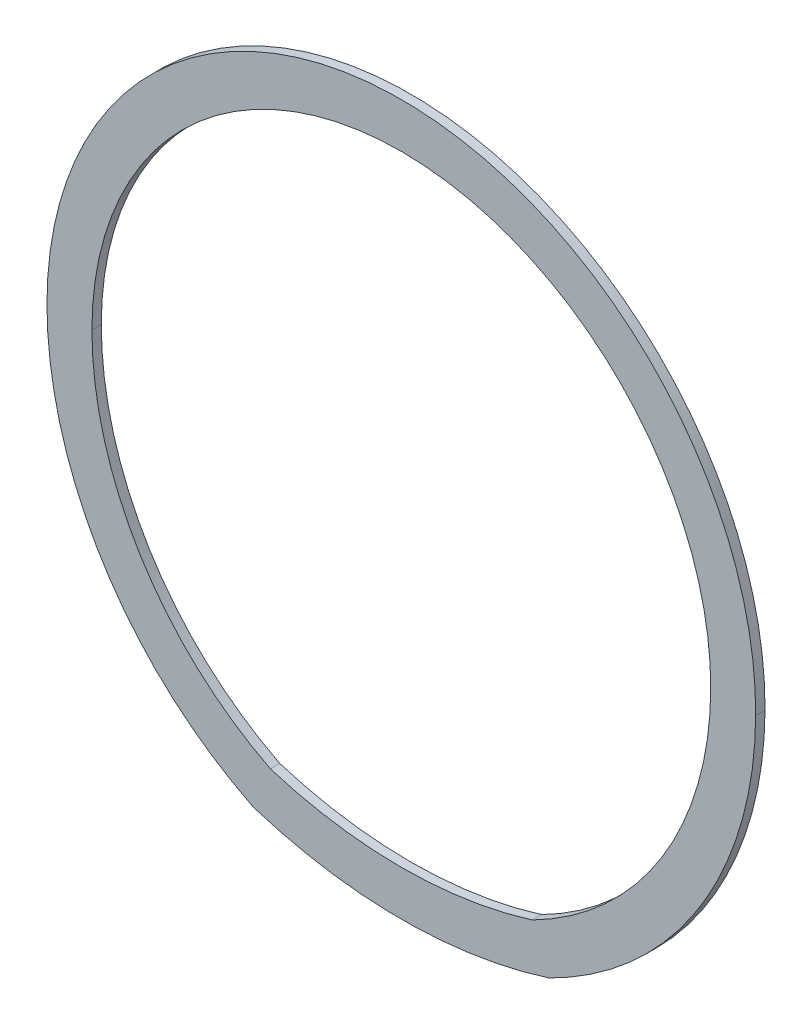
SolidWorks part; units mm, degrees
material "Balsa"
ref_plane "Front Plane" through (0, 0, 0) normal (0, 0, 1) x (1, 0, 0)
ref_plane "Top Plane" through (0, 0, 0) normal (0, 1, 0) x (1, 0, 0)
ref_plane "Right Plane" through (0, 0, 0) normal (1, 0, 0) x (0, 0, -1)
sketch "Sketch2" plane through (0, 0, 0) normal (0, 0, 1) x (1, 0, 0)
  line L0 (0, 0) -> (0.688, 245.4392) construction
  line L1 (-0.1309, -46.7153) -> (-0.2841, -101.3462) construction
  line L2 (0.0534, 19.05) -> (-169.3081, 19.05) construction
  line L3 (-72.7218, -93.726) -> (74.7111, -93.726) construction
  arc A1 (-120.0989, 19.05) -> (120.2036, 18.3433) centre (0.0534, 19.05) cw
  arc A2 (-120.0989, 19.05) -> (-50.0584, -93.726) centre (5.7147, 19.05) ccw
  arc A3 (-50.0584, -93.726) -> (50.1388, -93.726) centre (0.0402, 63.5) ccw
  arc A4 (120.2036, 18.3433) -> (50.1388, -93.726) centre (-5.6406, 19.0835) cw
  arc A5 (-104.8589, 19.05) -> (104.9639, 18.4329) centre (0.0534, 19.05) cw
  arc A6 (104.9639, 18.4329) -> (44.4049, -79.5534) centre (-5.6406, 19.0835) cw
  arc A7 (-44.324, -79.5535) -> (44.4049, -79.5534) centre (0.0402, 63.5) ccw
  arc A8 (-104.8589, 19.05) -> (-44.324, -79.5535) centre (5.7147, 19.05) ccw
  spline S0 degree 3 poles (-5521.0274, 5583.2546) (-1226.7801, 553.2855) (-196.9505, -260.8007) (69.4764, -82.4823) (75.8596, -77.7331) (81.7614, -72.3621) (85.2966, -68.8071) (85.996, -68.0862) (87.3792, -66.6243) (88.0639, -65.8824) (90.0847, -63.6371) (91.3894, -62.1126) (95.1787, -57.4581) (97.5389, -54.2471) (101.9343, -47.6137) (103.9694, -44.1914) (106.7765, -38.8981) (107.6712, -37.107) (109.3772, -33.4707) (110.1904, -31.6207) (112.481, -26.0415) (113.8153, -22.2742) (116.1105, -14.6467) (117.0712, -10.7866) (118.62, -2.9737) (119.208, 0.9791) (119.8028, 6.9796) (119.953, 8.9949) (120.1541, 13.0067) (120.2055, 15.0081) (120.2151, 20.9991) (119.8425, 28.9519) (118.7088, 36.835) (117.5685, 42.7208) (117.1399, 44.6783) (116.1841, 48.5842) (115.6559, 50.5346) (113.94, 56.3082) (112.6165, 60.0751) (109.6192, 67.4485) (107.9453, 71.055) (104.2453, 78.1066) (102.2192, 81.5518) (99.4588, 85.754) (98.8945, 86.5903) (97.7468, 88.2466) (97.1639, 89.0659) (95.3883, 91.4977) (94.1686, 93.0841) (90.4034, 97.7402) (87.752, 100.7072) (82.1689, 106.369) (79.2371, 109.0639) (74.6247, 112.8977) (73.0514, 114.1408) (70.6363, 115.9521) (69.821, 116.5478) (68.1799, 117.7153) (67.3537, 118.2875) (63.1947, 121.0918) (59.7778, 123.1535) (52.769, 126.9212) (49.1769, 128.6272) (41.816, 131.6806) (38.0473, 133.028) (33.2217, 134.4796) (32.2518, 134.758) (30.3116, 135.2882) (29.34, 135.5404) (26.4206, 136.2591) (24.4685, 136.6873) (18.5945, 137.8219) (14.6552, 138.3782) (6.7301, 139.0933) (2.7444, 139.252) (-2.2675, 139.1959) (-3.2714, 139.172) (-5.2821, 139.0983) (-6.2905, 139.0484) (-9.3072, 138.8606) (-11.3068, 138.6846) (-17.272, 138.0072) (-25.1357, 136.7069) (-32.823, 134.6274) (-38.5216, 132.7724) (-40.41, 132.1048) (-44.1641, 130.6694) (-46.0326, 129.9002) (-465.435, -55.3606) (264.7727, -2591.6725) (2155.1784, -7505.3224) knots -2.450405 -2.450405 -2.450405 -2.450405 0.03125 0.03125 0.0625 0.09375 0.09375 0.101563 0.101563 0.109375 0.109375 0.125 0.125 0.15625 0.15625 0.1875 0.1875 0.203125 0.203125 0.21875 0.21875 0.25 0.25 0.28125 0.28125 0.3125 0.3125 0.328125 0.328125 0.34375 0.34375 0.375 0.40625 0.40625 0.421875 0.421875 0.4375 0.4375 0.46875 0.46875 0.5 0.5 0.53125 0.53125 0.539063 0.539063 0.546875 0.546875 0.5625 0.5625 0.59375 0.59375 0.625 0.625 0.640625 0.640625 0.648438 0.648438 0.65625 0.65625 0.6875 0.6875 0.71875 0.71875 0.75 0.75 0.757813 0.757813 0.765625 0.765625 0.78125 0.78125 0.8125 0.8125 0.84375 0.84375 0.851563 0.851563 0.859375 0.859375 0.875 0.875 0.90625 0.9375 0.9375 0.953125 0.953125 0.96875 0.96875 4.508313 4.508313 4.508313 4.508313 only from (55.8537, -90.8749) to (-58.6671, 123.6507)
  spline S1 degree 3 poles (55.8537, -90.8749) (59.4151, -88.9779) (62.8499, -86.9173) (69.4764, -82.4823) (75.8596, -77.7331) (81.7614, -72.3621) (85.2966, -68.8071) (85.996, -68.0862) (87.3792, -66.6243) (88.0639, -65.8824) (90.0847, -63.6371) (91.3894, -62.1126) (95.1787, -57.4581) (97.5389, -54.2471) (101.9343, -47.6137) (103.9694, -44.1914) (106.7765, -38.8981) (107.6712, -37.107) (109.3772, -33.4707) (110.1904, -31.6207) (112.481, -26.0415) (113.8153, -22.2742) (116.1105, -14.6467) (117.0712, -10.7866) (118.62, -2.9737) (119.208, 0.9791) (119.8028, 6.9796) (119.953, 8.9949) (120.1541, 13.0067) (120.2055, 15.0081) (120.2151, 20.9991) (119.8425, 28.9519) (118.7088, 36.835) (117.5685, 42.7208) (117.1399, 44.6783) (116.1841, 48.5842) (115.6559, 50.5346) (113.94, 56.3082) (112.6165, 60.0751) (109.6192, 67.4485) (107.9453, 71.055) (104.2453, 78.1066) (102.2192, 81.5518) (99.4588, 85.754) (98.8945, 86.5903) (97.7468, 88.2466) (97.1639, 89.0659) (95.3883, 91.4977) (94.1686, 93.0841) (90.4034, 97.7402) (87.752, 100.7072) (82.1689, 106.369) (79.2371, 109.0639) (74.6247, 112.8977) (73.0514, 114.1408) (70.6363, 115.9521) (69.821, 116.5478) (68.1799, 117.7153) (67.3537, 118.2875) (63.1947, 121.0918) (59.7778, 123.1535) (52.769, 126.9212) (49.1769, 128.6272) (41.816, 131.6806) (38.0473, 133.028) (33.2217, 134.4796) (32.2518, 134.758) (30.3116, 135.2882) (29.34, 135.5404) (26.4206, 136.2591) (24.4685, 136.6873) (18.5945, 137.8219) (14.6552, 138.3782) (6.7301, 139.0933) (2.7444, 139.252) (-2.2675, 139.1959) (-3.2714, 139.172) (-5.2821, 139.0983) (-6.2905, 139.0484) (-9.3072, 138.8606) (-11.3068, 138.6846) (-17.272, 138.0072) (-25.1357, 136.7069) (-32.823, 134.6274) (-38.5216, 132.7724) (-40.41, 132.1048) (-44.1641, 130.6694) (-46.0326, 129.9002) (-51.5624, 127.4576) (-55.1595, 125.6458) (-58.6671, 123.6507) knots 0 0 0 0 0.03125 0.03125 0.0625 0.09375 0.09375 0.101563 0.101563 0.109375 0.109375 0.125 0.125 0.15625 0.15625 0.1875 0.1875 0.203125 0.203125 0.21875 0.21875 0.25 0.25 0.28125 0.28125 0.3125 0.3125 0.328125 0.328125 0.34375 0.34375 0.375 0.40625 0.40625 0.421875 0.421875 0.4375 0.4375 0.46875 0.46875 0.5 0.5 0.53125 0.53125 0.539063 0.539063 0.546875 0.546875 0.5625 0.5625 0.59375 0.59375 0.625 0.625 0.640625 0.640625 0.648438 0.648438 0.65625 0.65625 0.6875 0.6875 0.71875 0.71875 0.75 0.75 0.757813 0.757813 0.765625 0.765625 0.78125 0.78125 0.8125 0.8125 0.84375 0.84375 0.851563 0.851563 0.859375 0.859375 0.875 0.875 0.90625 0.9375 0.9375 0.953125 0.953125 0.96875 0.96875 1 1 1 1 construction
  spline S2 degree 3 poles (5694.5744, -5369.3669) (1292.3799, -516.6509) (187.1926, 314.492) (-76.9523, 111.0297) (-81.0984, 107.3558) (-85.9766, 102.3921) (-86.9369, 101.3807) (-88.8267, 99.3202) (-89.7577, 98.2691) (-92.4915, 95.0728) (-94.2304, 92.8907) (-99.2026, 86.1952) (-102.1931, 81.5333) (-106.1993, 74.2476) (-107.4545, 71.77) (-109.2154, 67.9791) (-109.782, 66.7031) (-110.874, 64.1258) (-111.4002, 62.8224) (-113.9097, 56.2871) (-115.5417, 50.9767) (-118.0823, 40.1978) (-118.9908, 34.7292) (-119.6657, 27.7928) (-119.7775, 26.4005) (-119.9543, 23.6055) (-120.0192, 22.2016) (-120.1418, 18.0057) (-120.1286, 15.2199) (-119.8102, 6.8959) (-119.2278, 1.3912) (-117.8014, -6.7994) (-117.2335, -9.5184) (-116.2404, -13.58) (-115.8858, -14.9311) (-115.1288, -17.6274) (-114.7258, -18.9739) (-112.6063, -25.6411) (-108.5276, -35.9696) (-103.1136, -45.6397) (-99.3011, -51.4722) (-98.5171, -52.628) (-96.9053, -54.9182) (-96.0765, -56.0537) (-93.5433, -59.4015) (-91.7865, -61.5635) (-86.3167, -67.8444) (-82.4051, -71.759) (-76.1398, -77.2217) (-73.9848, -78.9742) (-70.6503, -81.498) (-69.5218, -82.3217) (-67.2303, -83.9337) (-66.0665, -84.7222) (540.7318, -480.5341) (3882.3497, 5108.7967) (222.2795, -4616.5222) knots -3.63779 -3.63779 -3.63779 -3.63779 0.0625 0.0625 0.125 0.125 0.140625 0.140625 0.15625 0.15625 0.1875 0.1875 0.25 0.25 0.28125 0.28125 0.296875 0.296875 0.3125 0.3125 0.375 0.375 0.4375 0.4375 0.453125 0.453125 0.46875 0.46875 0.5 0.5 0.5625 0.5625 0.59375 0.59375 0.609375 0.609375 0.625 0.625 0.6875 0.75 0.75 0.765625 0.765625 0.78125 0.78125 0.8125 0.8125 0.875 0.875 0.90625 0.90625 0.921875 0.921875 0.9375 0.9375 9.012836 9.012836 9.012836 9.012836 only from (-58.6671, 123.6507) to (-50.3455, -93.5936)
  spline S3 degree 3 poles (-4578.1193, 6360.5009) (1102.8247, -3189.0685) (1357.3206, -1629.0846) (-2110.3169, 7551.2134) knots -196.711406 -196.711406 -196.711406 -196.711406 209.883914 209.883914 209.883914 209.883914 only from (49.819, -93.8744) to (55.8537, -90.8749)
  spline S4 degree 3 poles (49.819, -93.8744) (51.8584, -92.9316) (53.87, -91.9317) (55.8537, -90.8749) knots 0 0 0 0 1 1 1 1 construction
  spline S5 degree 3 poles (-58.6671, 123.6507) (-63.5487, 120.874) (-68.1774, 117.7887) (-76.9523, 111.0297) (-81.0984, 107.3558) (-85.9766, 102.3921) (-86.9369, 101.3807) (-88.8267, 99.3202) (-89.7577, 98.2691) (-92.4915, 95.0728) (-94.2304, 92.8907) (-99.2026, 86.1952) (-102.1931, 81.5333) (-106.1993, 74.2476) (-107.4545, 71.77) (-109.2154, 67.9791) (-109.782, 66.7031) (-110.874, 64.1258) (-111.4002, 62.8224) (-113.9097, 56.2871) (-115.5417, 50.9767) (-118.0823, 40.1978) (-118.9908, 34.7292) (-119.6657, 27.7928) (-119.7775, 26.4005) (-119.9543, 23.6055) (-120.0192, 22.2016) (-120.1418, 18.0057) (-120.1286, 15.2199) (-119.8102, 6.8959) (-119.2278, 1.3912) (-117.8014, -6.7994) (-117.2335, -9.5184) (-116.2404, -13.58) (-115.8858, -14.9311) (-115.1288, -17.6274) (-114.7258, -18.9739) (-112.6063, -25.6411) (-108.5276, -35.9696) (-103.1136, -45.6397) (-99.3011, -51.4722) (-98.5171, -52.628) (-96.9053, -54.9182) (-96.0765, -56.0537) (-93.5433, -59.4015) (-91.7865, -61.5635) (-86.3167, -67.8444) (-82.4051, -71.759) (-76.1398, -77.2217) (-73.9848, -78.9742) (-70.6503, -81.498) (-69.5218, -82.3217) (-67.2303, -83.9337) (-66.0665, -84.7222) (-60.2073, -88.5441) (-55.3561, -91.2432) (-50.3455, -93.5936) knots 0 0 0 0 0.0625 0.0625 0.125 0.125 0.140625 0.140625 0.15625 0.15625 0.1875 0.1875 0.25 0.25 0.28125 0.28125 0.296875 0.296875 0.3125 0.3125 0.375 0.375 0.4375 0.4375 0.453125 0.453125 0.46875 0.46875 0.5 0.5 0.5625 0.5625 0.59375 0.59375 0.609375 0.609375 0.625 0.625 0.6875 0.75 0.75 0.765625 0.765625 0.78125 0.78125 0.8125 0.8125 0.875 0.875 0.90625 0.90625 0.921875 0.921875 0.9375 0.9375 1 1 1 1 construction
  spline S6 degree 3 poles (-1759.0643, 7695.5768) (129.301, 75.0658) (104.9025, -75.6984) (45.8458, -95.3665) (44.8322, -95.6594) (41.7708, -96.4587) (39.7032, -96.8873) (35.5384, -97.6293) (33.4392, -97.9405) (29.2422, -98.4783) (27.1412, -98.7049) (20.8322, -99.2882) (16.6185, -99.55) (8.1799, -99.8877) (3.9548, -99.9623) (-4.5058, -99.9387) (-8.734, -99.8405) (-17.1695, -99.4557) (-21.3793, -99.1705) (-27.6778, -98.553) (-29.7745, -98.3152) (-33.9608, -97.7556) (-36.0504, -97.4344) (-39.177, -96.8603) (-40.2191, -96.653) (-42.292, -96.1992) (-43.3225, -95.953) (-45.3676, -95.407) (-46.3821, -95.1076) (-105.8729, -74.9194) (-124.4058, 77.5041) (2082.3243, 7613.4914) knots -1.777254 -1.777254 -1.777254 -1.777254 0.03125 0.03125 0.0625 0.0625 0.125 0.125 0.1875 0.1875 0.25 0.25 0.375 0.375 0.5 0.5 0.625 0.625 0.75 0.75 0.8125 0.8125 0.875 0.875 0.90625 0.90625 0.9375 0.9375 0.96875 0.96875 2.792352 2.792352 2.792352 2.792352 only from (49.8185, -93.8746) to (-50.3451, -93.5938)
  spline S7 degree 3 poles (49.8185, -93.8746) (48.8452, -94.325) (47.8521, -94.6984) (45.8458, -95.3665) (44.8322, -95.6594) (41.7708, -96.4587) (39.7032, -96.8873) (35.5384, -97.6293) (33.4392, -97.9405) (29.2422, -98.4783) (27.1412, -98.7049) (20.8322, -99.2882) (16.6185, -99.55) (8.1799, -99.8877) (3.9548, -99.9623) (-4.5058, -99.9387) (-8.734, -99.8405) (-17.1695, -99.4557) (-21.3793, -99.1705) (-27.6778, -98.553) (-29.7745, -98.3152) (-33.9608, -97.7556) (-36.0504, -97.4344) (-39.177, -96.8603) (-40.2191, -96.653) (-42.292, -96.1992) (-43.3225, -95.953) (-45.3676, -95.407) (-46.3821, -95.1076) (-48.3867, -94.4274) (-49.3773, -94.0483) (-50.3451, -93.5938) knots 0 0 0 0 0.03125 0.03125 0.0625 0.0625 0.125 0.125 0.1875 0.1875 0.25 0.25 0.375 0.375 0.5 0.5 0.625 0.625 0.75 0.75 0.8125 0.8125 0.875 0.875 0.90625 0.90625 0.9375 0.9375 0.96875 0.96875 1 1 1 1 construction
  spline S8 degree 1 poles (44.4895, -82.3468) (49.8828, -79.6661) knots 0 0 1 1 construction
  spline S9 degree 1 poles (49.8828, -79.6661) (-52.388, 112.6115) knots 0 0 1 1 construction
  spline S10 degree 1 poles (-52.388, 112.6115) (-44.952, -82.0958) knots 0 0 1 1 construction
  spline S11 degree 3 poles (44.4895, -82.3468) (44.9451, -82.1361) (45.8533, -81.7084) (47.2062, -81.0479) (48.5497, -80.3682) (49.4396, -79.9022) (49.8828, -79.6661) knots 0 0 0 0 0.250007 0.500014 0.750021 1.000028 1.000028 1.000028 1.000028 construction
  spline S12 degree 3 poles (49.8828, -79.6661) (51.4682, -78.8216) (54.6039, -77.0481) (60.6329, -73.2256) (67.7713, -67.9145) (75.6946, -60.7068) (85.376, -49.946) (92.2499, -39.5527) (97.0635, -29.9209) (99.9774, -23.2906) (102.9687, -14.8438) (105.5551, -4.452) (106.8747, 4.4138) (107.4138, 11.642) (107.598, 18.8242) (107.1791, 27.7507) (105.6575, 38.3493) (103.0737, 48.9109) (99.5091, 59.0529) (95.0071, 68.7524) (90.4672, 76.4728) (86.3465, 82.4205) (79.7918, 90.9419) (71.0678, 99.805) (59.5047, 108.4813) (50.3361, 114.0108) (40.7123, 118.5824) (32.2831, 121.5955) (25.3334, 123.4944) (18.366, 125.0225) (9.571, 126.2643) (-1.0997, 126.6912) (-11.9104, 126.0185) (-22.4327, 124.2743) (-36.1547, 120.5693) (-46.1487, 116.1604) (-52.388, 112.6115) knots 0 0 0 0 0.015625 0.03125 0.0625 0.09375 0.125 0.1875 0.203125 0.21875 0.25 0.28125 0.3125 0.328125 0.34375 0.375 0.40625 0.4375 0.46875 0.5 0.53125 0.546875 0.5625 0.625 0.65625 0.6875 0.71875 0.75 0.765625 0.78125 0.8125 0.84375 0.875 0.90625 0.9375 1 1 1 1 construction
  spline S13 degree 3 poles (-52.388, 112.6115) (-54.5585, 111.3769) (-58.8261, 108.7475) (-66.8816, 102.9693) (-76.1597, 94.757) (-85.9932, 83.258) (-92.681, 72.8203) (-97.1816, 63.9424) (-101.112, 54.6656) (-104.776, 42.7383) (-106.8137, 30.488) (-107.4512, 20.4245) (-107.4028, 10.4189) (-106.3564, 0.5368) (-104.3212, -9.2152) (-101.5955, -18.9231) (-97.0158, -30.5128) (-90.9605, -41.334) (-85.1677, -49.567) (-78.8706, -57.3154) (-71.8665, -64.3232) (-64.1621, -70.5906) (-57.9948, -74.9291) (-51.5954, -78.7902) (-47.193, -81.0446) (-44.952, -82.0958) knots 0 0 0 0 0.03125 0.0625 0.125 0.1875 0.25 0.28125 0.3125 0.375 0.4375 0.46875 0.5 0.5625 0.59375 0.625 0.6875 0.75 0.78125 0.8125 0.875 0.90625 0.9375 0.96875 1 1 1 1 construction
  spline S14 degree 1 poles (44.4849, -82.3489) (-44.9469, -82.0982) knots 0 0 1 1 construction
  spline S15 degree 3 poles (44.4849, -82.3489) (44.3746, -82.3999) (44.1627, -82.4934) (43.6492, -82.7012) (42.8561, -82.9839) (41.7841, -83.3184) (40.2245, -83.7477) (38.1103, -84.2445) (35.4106, -84.7656) (32.6063, -85.224) (28.7759, -85.7537) (23.885, -86.2821) (17.9201, -86.7432) (11.8971, -87.0512) (5.8396, -87.2261) (-2.2666, -87.2864) (-10.3738, -87.0974) (-18.3985, -86.6419) (-24.3556, -86.1481) (-29.2377, -85.5934) (-33.056, -85.0443) (-35.8555, -84.5718) (-38.5671, -84.0318) (-40.6899, -83.5223) (-42.2517, -83.0828) (-43.3238, -82.7417) (-44.1147, -82.4546) (-44.6269, -82.2439) (-44.8373, -82.1497) (-44.9469, -82.0982) knots 0 0 0 0 0.007812 0.015625 0.03125 0.046875 0.0625 0.09375 0.125 0.15625 0.1875 0.25 0.3125 0.375 0.4375 0.5 0.625 0.6875 0.75 0.8125 0.84375 0.875 0.90625 0.9375 0.953125 0.96875 0.984375 0.992188 1 1 1 1 construction
  point P12 (-0.2802, -99.9505)
  dimension "D3" = 19.05
  dimension "D4" = 93.726
  dimension "D5" = 63.5
  dimension "D6" = 15.24
  dimension "D1" = 12.7
  dimension "D2" = 12.7
extrude "Boss-Extrude1" add sketch "Sketch2" along normal mid plane 3.175
